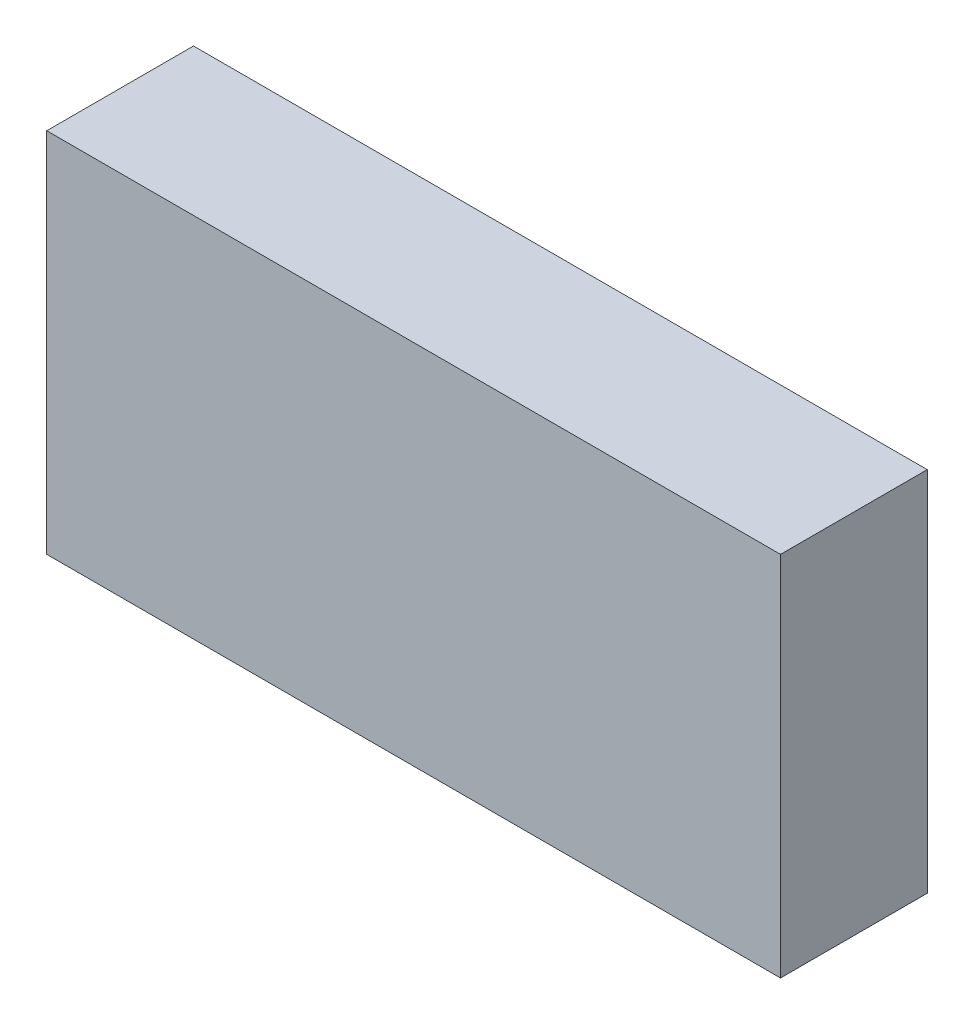
SolidWorks part; units mm, degrees
ref_plane "Front Plane" through (0, 0, 0) normal (0, 0, 1) x (1, 0, 0)
ref_plane "Top Plane" through (0, 0, 0) normal (0, 1, 0) x (1, 0, 0)
ref_plane "Right Plane" through (0, 0, 0) normal (1, 0, 0) x (0, 0, -1)
other "Configuration Table"
sketch "Sketch1" plane through (0, 0, 0) normal (0, 0, 1) x (1, 0, 0)
  line L1 (300, 30) -> (600, 30)
  line L2 (300, 30) -> (300, 180)
  line L3 (300, 180) -> (600, 180)
  line L4 (600, 30) -> (600, 180)
extrude "TOPPING_sog_kondenser_1" add sketch "Sketch1" against normal blind 60 from offset 240 separate body
